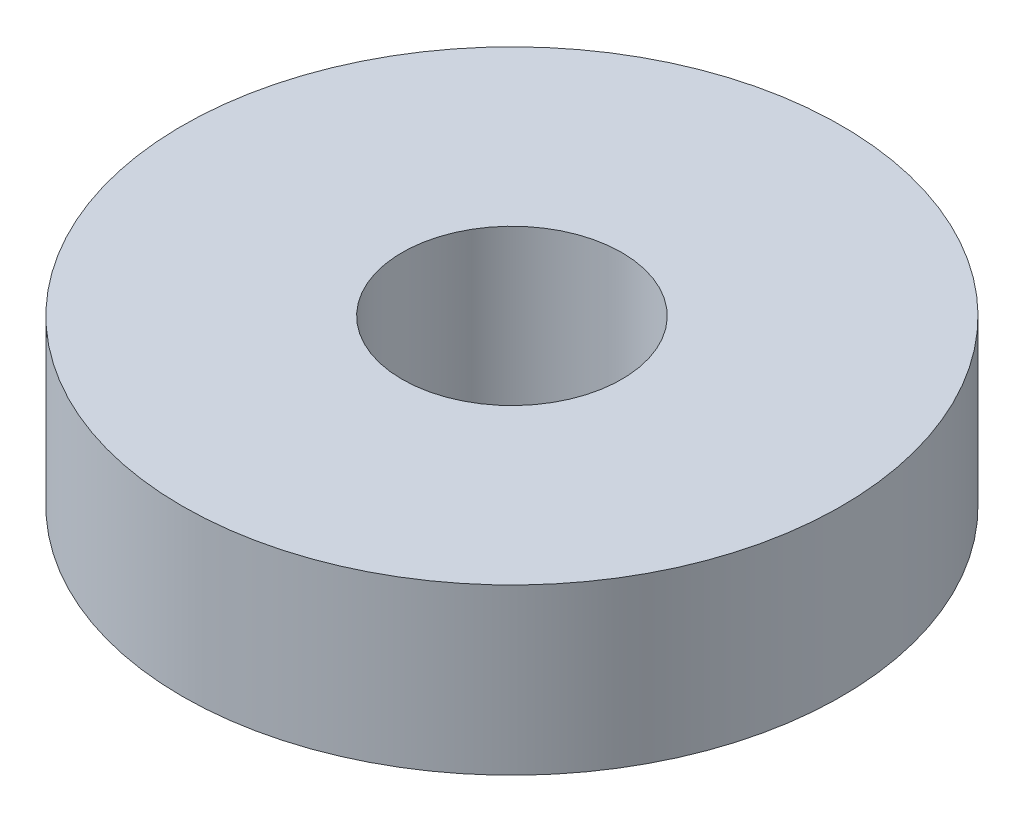
SolidWorks part; units mm, degrees
ref_plane "Front Plane" through (0, 0, 0) normal (0, 0, 1) x (1, 0, 0)
ref_plane "Top Plane" through (0, 0, 0) normal (0, 1, 0) x (1, 0, 0)
ref_plane "Right Plane" through (0, 0, 0) normal (1, 0, 0) x (0, 0, -1)
sketch "Sketch1" plane through (0, 0, 0) normal (0, 1, 0) x (1, 0, 0)
  circle A0 centre (0, 0) radius 4
  circle A1 centre (0, 0) radius 12
  dimension "D1" = 24
  dimension "D2" = 8
extrude "Boss-Extrude1" add sketch "Sketch1" along normal blind 6
